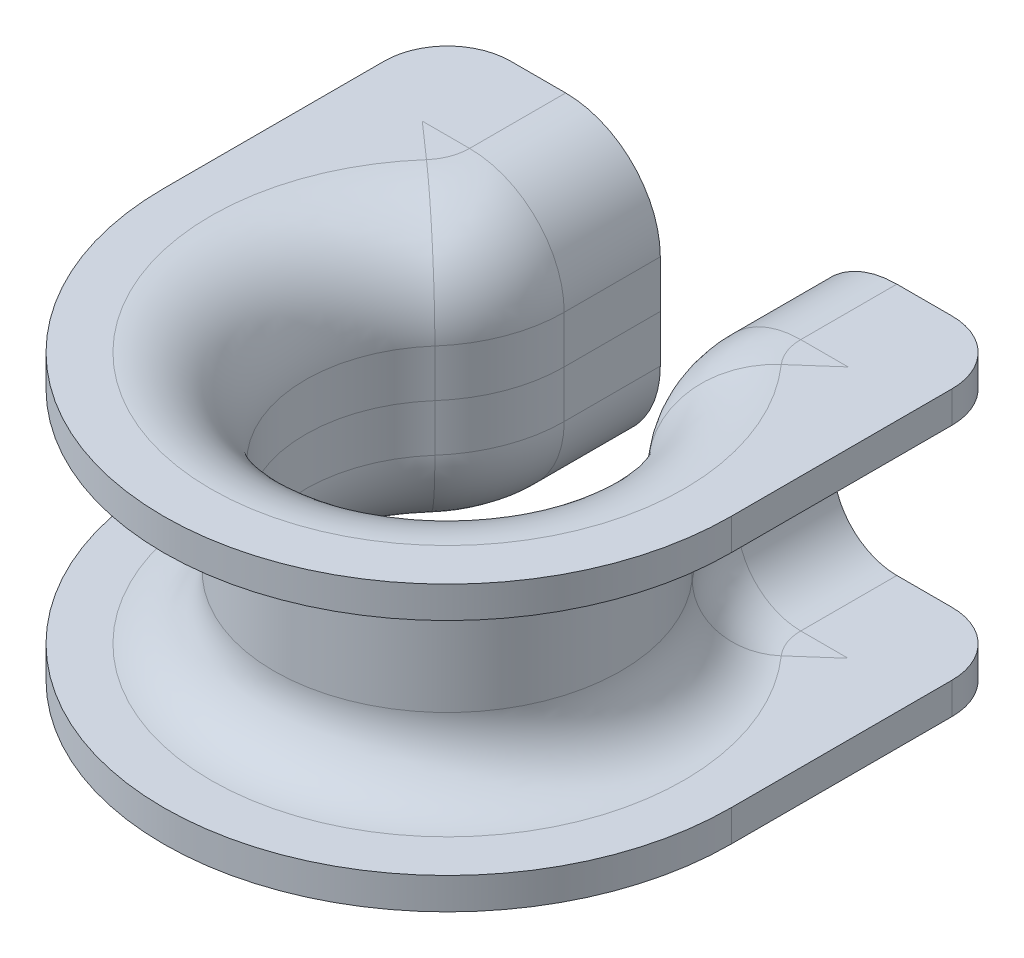
SolidWorks part; units mm, degrees
ref_plane "Front Plane" through (0, 0, 0) normal (0, 0, 1) x (1, 0, 0)
ref_plane "Top Plane" through (0, 0, 0) normal (0, 1, 0) x (1, 0, 0)
ref_plane "Right Plane" through (0, 0, 0) normal (1, 0, 0) x (0, 0, -1)
sketch "Sketch1" plane through (0, 0, 0) normal (0, 1, 0) x (1, 0, 0)
  line L0 (-4.5, 18) -> (-4.5, 11.9059)
  line L1 (4.5, 18) -> (4.5, 11.9059)
  line L3 (0, 43.3217) -> (0, 70.8275) construction
  arc A0 (-4.5, 11.9059) -> (-6.75, 5.9529) centre (-13.5, 11.9059) cw
  arc A1 (-6.75, 5.9529) -> (6.75, 5.9529) centre (0, 0) ccw
  arc A2 (4.5, 11.9059) -> (6.75, 5.9529) centre (13.5, 11.9059) ccw
  point P18 (0, -9)
  dimension "D1" = 9
  dimension "D2" = 18
  dimension "D3" = 4.5
  dimension "D4" = 9
sketch "Sketch3" plane through (0, 0, 0) normal (1, 0, 0) x (0, 0, -1)
  line L0 (-18, 9) -> (-15, 9)
  line L1 (-9, 3) -> (-9, 0)
  line L4 (5.9529, 0) -> (-9, 0) construction
  line L5 (-18, 7) -> (-15, 7)
  line L6 (-11, 3) -> (-11, -3)
  line L7 (-11, 3) -> (-11, 0) construction
  line L8 (-199956.6783, 0) -> (200070.8275, 0) construction
  line L9 (14.3623, 0) -> (10.9169, 0) construction
  line L10 (-18, -7) -> (-15, -7)
  line L11 (-9, -3) -> (-9, 0)
  line L12 (-18, -9) -> (-15, -9)
  line L13 (-18, 9) -> (-18, 7)
  line L14 (-18, -7) -> (-18, -9)
  arc A0 (-15, 9) -> (-9, 3) centre (-15, 3) cw
  arc A1 (-15, 7) -> (-11, 3) centre (-15, 3) cw
  arc A2 (-15, -7) -> (-11, -3) centre (-15, -3) ccw
  arc A3 (-15, -9) -> (-9, -3) centre (-15, -3) ccw
  point P16 (-11, 0)
  point P24 (-9.019, 0)
  point P27 (-9.2617, 3)
  point P29 (0, 0)
  dimension "D3" = 9
  dimension "D1" = 6
  dimension "D2" = 3
  dimension "D4" = 2
  dimension "D5" = 90
sweep "Sweep1" add profiles "Sketch3" path "Sketch1"
sketch "Sketch4" plane through (0, 0, -18) normal (0, 0, -1) x (-1, 0, 0)
  line L0 (-13.5, 9) -> (-18, 9)
  line L1 (-18, 9) -> (-18, 7)
  line L2 (-18, 7) -> (-13.5, 7)
  line L3 (-13.5, 7) -> (-13.5, 9)
  line L4 (-13.5, -9) -> (-18, -9)
  line L5 (-18, -9) -> (-18, -7)
  line L6 (-18, -7) -> (-13.5, -7)
  line L7 (-13.5, -7) -> (-13.5, -9)
  line L8 (13.5, 9) -> (13.5, 7)
  line L9 (13.5, 7) -> (18, 7)
  line L10 (18, 7) -> (18, 9)
  line L11 (18, 9) -> (13.5, 9)
  line L12 (13.5, -7) -> (13.5, -9)
  line L13 (13.5, -9) -> (18, -9)
  line L14 (18, -9) -> (18, -7)
  line L15 (18, -7) -> (13.5, -7)
  line M1 (13.5, 7) -> (13.5, 9)
  line M8 (13.5, -9) -> (13.5, -7)
extrude "Boss-Extrude1" add sketch "Sketch4" against normal up to surface (18 mm away) contours L2 L3 L0 L1 | L10 L11 L9 M1 | L14 L15 L13 M8 | L7 L6 L5 L4
fillet "Fillet1" radius 4 4 edges at (-18, -8, -18) (-18, 8, -18) (18, -8, -18) (18, 8, -18)
